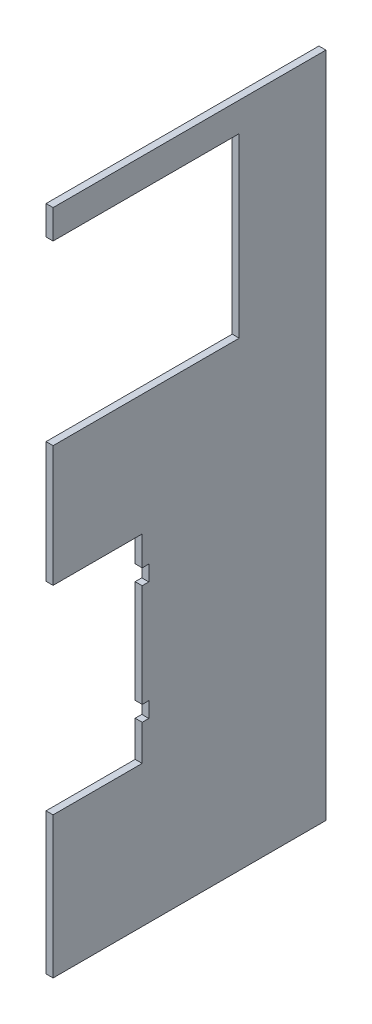
SolidWorks part; units mm, degrees
ref_plane "Спереди" through (0, 0, 0) normal (0, 0, 1) x (1, 0, 0)
ref_plane "Сверху" through (0, 0, 0) normal (0, 1, 0) x (1, 0, 0)
ref_plane "Справа" through (0, 0, 0) normal (1, 0, 0) x (0, 0, -1)
ref_plane "Плоскость4" through (0.5, 0, 0) normal (-1, 0, 0) x (0, -1, 0)
sketch "Эскиз1" plane through (0.5, 0, 0) normal (-1, 0, 0) x (0, -1, 0)
  line L0 (-5.85, 42.25) -> (-100.85, 42.25)
  line L1 (-100.85, 42.25) -> (-100.85, 3.4)
  line L2 (-100.85, 3.4) -> (-5.85, 3.4)
  line L3 (-5.85, 3.4) -> (-5.85, 42.25)
extrude "Бобышка-Вытянуть1" add sketch "Эскиз1" against normal blind 0.5
sketch "Эскиз2" plane through (0.5, 0, 0) normal (-1, 0, 0) x (0, 0, 1)
  line L0 (42.25, 5.85) -> (3.4, 5.85)
  line L1 (3.4, 5.85) -> (3.4, 100.85)
  line L2 (3.4, 100.85) -> (42.25, 100.85)
  line L3 (42.25, 100.85) -> (42.25, 5.85)
extrude "Бобышка-Вытянуть2" add sketch "Эскиз2" along normal blind 0.5
sketch "Эскиз3" plane through (0, 0, 0) normal (-1, 0, 0) x (0, 0, 1)
  line L1 (47.1872, 54.262) -> (29.5623, 54.262)
  line L2 (47.1872, 54.262) -> (47.1872, 25.9692)
  line L3 (47.1872, 25.9692) -> (29.5623, 25.9692)
  line L4 (29.5623, 54.262) -> (29.5623, 25.9692) construction
  line L5 (29.5623, 54.262) -> (29.5623, 50.0787)
  line L10 (29.5623, 50.0787) -> (28.6189, 50.0787)
  line L11 (28.6189, 50.0787) -> (28.6189, 47.8787)
  line L12 (28.6189, 47.8787) -> (29.5623, 47.8787)
  line L13 (29.5623, 47.8787) -> (29.5623, 33.2387)
  line L14 (29.5623, 33.2387) -> (28.6189, 33.2387)
  line L15 (28.6189, 33.2387) -> (28.6189, 31.0387)
  line L16 (28.6189, 31.0387) -> (29.5623, 31.0387)
  line L17 (29.5623, 31.0387) -> (29.5623, 25.9692)
  line L18 (28.9189, 49.7787) -> (31.0057, 49.7787) construction
  line L19 (28.9189, 48.1787) -> (28.9189, 49.7787) construction
  line L20 (31.0057, 48.1787) -> (28.9189, 48.1787) construction
  line L21 (28.9189, 32.9387) -> (31.0057, 32.9387) construction
  line L22 (28.9189, 31.3387) -> (28.9189, 32.9387) construction
  line L23 (31.0057, 31.3387) -> (28.9189, 31.3387) construction
  line L24 (15.7453, 96.7207) -> (47.1872, 96.7207)
  line L25 (15.7453, 96.7207) -> (15.7453, 71.4933)
  line L26 (15.7453, 71.4933) -> (47.1872, 71.4933)
  line L27 (47.1872, 96.7207) -> (47.1872, 71.4933)
  dimension "D1" = 0.3
  dimension "D2" = 0.3
  dimension "D3" = 0.3
  dimension "D4" = 0.3
  dimension "D5" = 0.3
  dimension "D6" = 0.3
extrude "Вырез-Вытянуть1" cut sketch "Эскиз3" against normal through all
